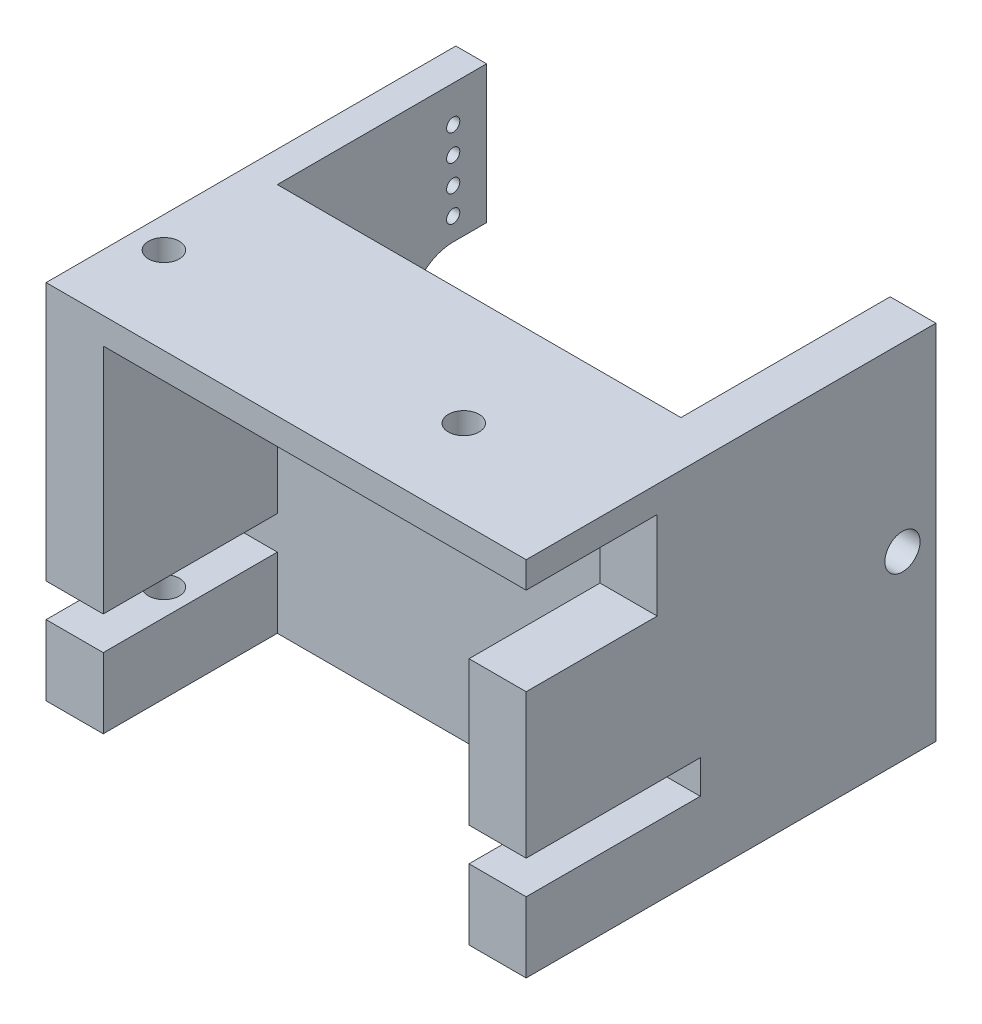
SolidWorks part; units mm, degrees
ref_plane "前基準面" through (0, 0, 0) normal (0, 0, 1) x (1, 0, 0)
ref_plane "上基準面" through (0, 0, 0) normal (0, 1, 0) x (1, 0, 0)
ref_plane "右基準面" through (0, 0, 0) normal (1, 0, 0) x (0, 0, -1)
sketch "草圖1" plane through (0, 0, 0) normal (0, 0, 1) x (1, 0, 0)
  line L0 (-48.1, 39.2) -> (-48.1, 12.8)
  line L1 (0, 1) -> (-6.5, 1)
  line L2 (0, 12.8) -> (-6.5, 12.8)
  line L3 (0, 42.2) -> (-7, 42.2)
  line L4 (-54.6, 1) -> (-54.6, 9)
  line L5 (0, 9) -> (-6.5, 9)
  line L6 (-54.6, 9) -> (-48.1, 9)
  line L7 (-54.6, 12.8) -> (-48.1, 12.8)
  line L8 (-48.1, 9) -> (-48.1, 1)
  line L9 (0, 1) -> (0, 9)
  line L10 (-6.5, 39.2) -> (-6.5, 12.8)
  line L11 (-54.6, 12.8) -> (-54.6, 42.2)
  line L12 (-47.6, 42.2) -> (-54.6, 42.2)
  line L13 (-48.1, 1) -> (-54.6, 1)
  line L14 (0, 12.8) -> (0, 42.2)
  line L15 (-6.5, 9) -> (-6.5, 1)
  line L17 (-47.6, 42.2) -> (-7, 42.2)
  line L19 (-48.1, 39.2) -> (-6.5, 39.2)
  dimension "D1" = 3
  dimension "D2" = 41.2
  dimension "D3" = 6.5
  dimension "D5" = 26.4
  dimension "D6" = 3.8
  dimension "D7" = 3.8
  dimension "D8" = 54.6
  dimension "D9" = 6.5
  dimension "D10" = 26.4
extrude "填料-伸長1" add sketch "草圖1" along normal blind 19.8
sketch "草圖2" plane through (0, 0, 0) normal (0, 0, -1) x (-1, 0, 0)
  line L1 (0, 42.2) -> (54.6, 42.2)
  line L2 (0, 42.2) -> (0, 1)
  line L3 (0, 1) -> (54.6, 1)
  line L4 (54.6, 42.2) -> (54.6, 1)
extrude "填料-伸長2" add sketch "草圖2" along normal blind 3
sketch "草圖4" plane through (-54.6, 54.6, 0) normal (1, 0, 0) x (0, -1, 0)
  line L0 (12.4, 26.8) -> (28.05, 26.8)
  line L1 (53.6, 3) -> (12.4, 3)
  line L2 (53.6, 3) -> (53.6, 23)
  line L3 (28.05, 26.8) -> (28.05, 23)
  line L4 (12.4, 3) -> (12.4, 23)
  line L5 (12.4, 3) -> (12.4, -19.8) construction
  line L6 (53.6, 26.8) -> (53.6, 23)
  line L7 (37.95, 23) -> (37.95, 26.8)
  line L8 (12.4, 26.8) -> (12.4, 23)
  line L9 (37.95, 26.8) -> (53.6, 26.8)
  arc A0 (28.05, 23) -> (37.95, 23) centre (33, 23) ccw
  circle A1 centre (40.5, 23) radius 0.75
  circle A2 centre (43.5, 23) radius 0.75
  circle A3 centre (46.5, 23) radius 0.75
  circle A4 centre (49.5, 23) radius 0.75
  circle A5 centre (16.5, 23) radius 0.75
  circle A6 centre (19.5, 23) radius 0.75
  circle A7 centre (22.5, 23) radius 0.75
  circle A8 centre (25.5, 23) radius 0.75
  point P30 (33, 3)
  dimension "D1" = 1.5
  dimension "D2" = 7.5
  dimension "D3" = 3
  dimension "D4" = 3
  dimension "D5" = 3
  dimension "D6" = 3
  dimension "D7" = 3
  dimension "D8" = 3
  dimension "D10" = 0
  dimension "D11" = 7.5
  dimension "D12" = 4.95
  dimension "D13" = 1.5
  dimension "D9" = 0
extrude "填料-伸長3" add sketch "草圖4" along normal blind 3.5
sketch "草圖5" plane through (0, 0, 0) normal (1, 0, 0) x (0, 0, -1)
  line L0 (26.8, 42.2) -> (26.8, 1)
  line L1 (3, 42.2) -> (26.8, 42.2)
  line L2 (3, 42.2) -> (3, 1)
  line L3 (26.8, 1) -> (-19.8, 1) construction
  line L4 (26.8, 1) -> (3, 1)
extrude "填料-伸長4" add sketch "草圖5" against normal blind 5.2
sketch "草圖6" plane through (0, 1, 0) normal (0, -1, 0) x (-1, 0, 0)
  line L0 (54.6, -19.8) -> (48.1, -19.8) construction
  line L1 (48.1, -19.8) -> (48.1, 0) construction
  circle A0 centre (51.1, -9.9) radius 1.75
  dimension "D1" = 3.5
  dimension "D2" = 9.9
  dimension "D3" = 3
extrude "除料-伸長2" cut sketch "草圖6" against normal up to surface (8 mm away) up to face at (-51.35, 9, 9.9)
sketch "草圖7" plane through (0, 42.2, 0) normal (0, 1, 0) x (1, 0, 0)
  line L0 (-54.6, 26.8) -> (-54.6, -19.8) construction
  line L1 (0, -19.8) -> (-54.6, -19.8) construction
  line L2 (0, 26.8) -> (0, -19.8) construction
  circle A0 centre (-51.1, -9.9) radius 1.75
  circle A1 centre (-17, -9.9) radius 1.75
  dimension "D1" = 3.5
  dimension "D2" = 3.5
  dimension "D3" = 9.9
  dimension "D4" = 3.5
  dimension "D5" = 17
  dimension "D6" = 9.9
extrude "除料-伸長3" cut sketch "草圖7" against normal blind 8
sketch "草圖9" plane through (0, 0, 0) normal (1, 0, 0) x (0, 0, -1)
  line L0 (26.8, 42.2) -> (3, 42.2) construction
  circle A0 centre (23, 21.6) radius 2
  dimension "D1" = 20.6
  dimension "D2" = 4
extrude "除料-伸長4" cut sketch "草圖9" against normal blind 10
sketch "草圖10" plane through (0, 0, 0) normal (1, 0, 0) x (0, 0, -1)
  line L0 (26.8, 42.2) -> (-19.8, 42.2) construction
  line L1 (-4.9, 39.2) -> (-19.8, 39.2)
  line L2 (-19.8, 39.2) -> (-19.8, 29.2)
  line L3 (-19.8, 29.2) -> (-4.9, 29.2)
  line L4 (-4.9, 39.2) -> (-4.9, 29.2)
  line L6 (-19.8, 12.8) -> (-19.8, 42.2) construction
  dimension "D1" = 13
  dimension "D2" = 14.9
  dimension "D3" = 10
extrude "除料-伸長5" cut sketch "草圖10" against normal blind 7
